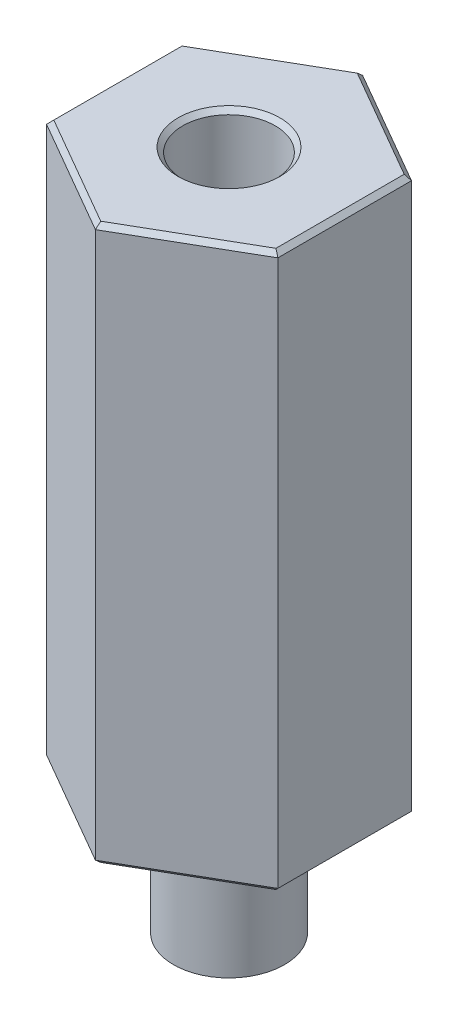
SolidWorks part; units mm, degrees
ref_plane "Front Plane" through (0, 0, 0) normal (0, 0, 1) x (1, 0, 0)
ref_plane "Top Plane" through (0, 0, 0) normal (0, 1, 0) x (1, 0, 0)
ref_plane "Right Plane" through (0, 0, 0) normal (1, 0, 0) x (0, 0, -1)
sketch "Sketch1" plane through (0, 0, 0) normal (0, 1, 0) x (1, 0, 0)
  line L1 (0, 2.8868) -> (-2.5, 1.4434)
  line L2 (-2.5, 1.4434) -> (-2.5, -1.4434)
  line L3 (-2.5, -1.4434) -> (0, -2.8868)
  line L4 (0, -2.8868) -> (2.5, -1.4434)
  line L5 (2.5, -1.4434) -> (2.5, 1.4434)
  line L6 (2.5, 1.4434) -> (0, 2.8868)
  circle A0 centre (0, 0) radius 2.5 construction
  dimension "D1" = 5
extrude "Boss-Extrude1" add sketch "Sketch1" along normal blind 12
sketch "Sketch2" plane through (0, 12, 0) normal (0, 1, 0) x (1, 0, 0)
  circle A0 centre (0, 0) radius 1
  dimension "D1" = 2
extrude "Cut-Extrude1" cut sketch "Sketch2" against normal through all
chamfer "Chamfer1" distance 0.1 angle 45 13 edges at (2.5, 12, 0) (1.25, 12, 2.1651) (-1.25, 12, 2.1651) (-2.5, 12, 0) (-1.25, 12, -2.1651) (1.25, 12, -2.1651) (0, 12, 1) (-1.25, 0, 2.1651) (1.25, 0, 2.1651) (2.5, 0, 0) (1.25, 0, -2.1651) (-1.25, 0, -2.1651) (-2.5, 0, 0)
sketch "Sketch3" plane through (0, 0, 0) normal (0, -1, 0) x (1, 0, 0)
  circle A0 centre (0, 0) radius 1.2
  dimension "D1" = 2.4
extrude "Boss-Extrude2" add sketch "Sketch3" along normal blind 2.7 and the other way blind 2.7
